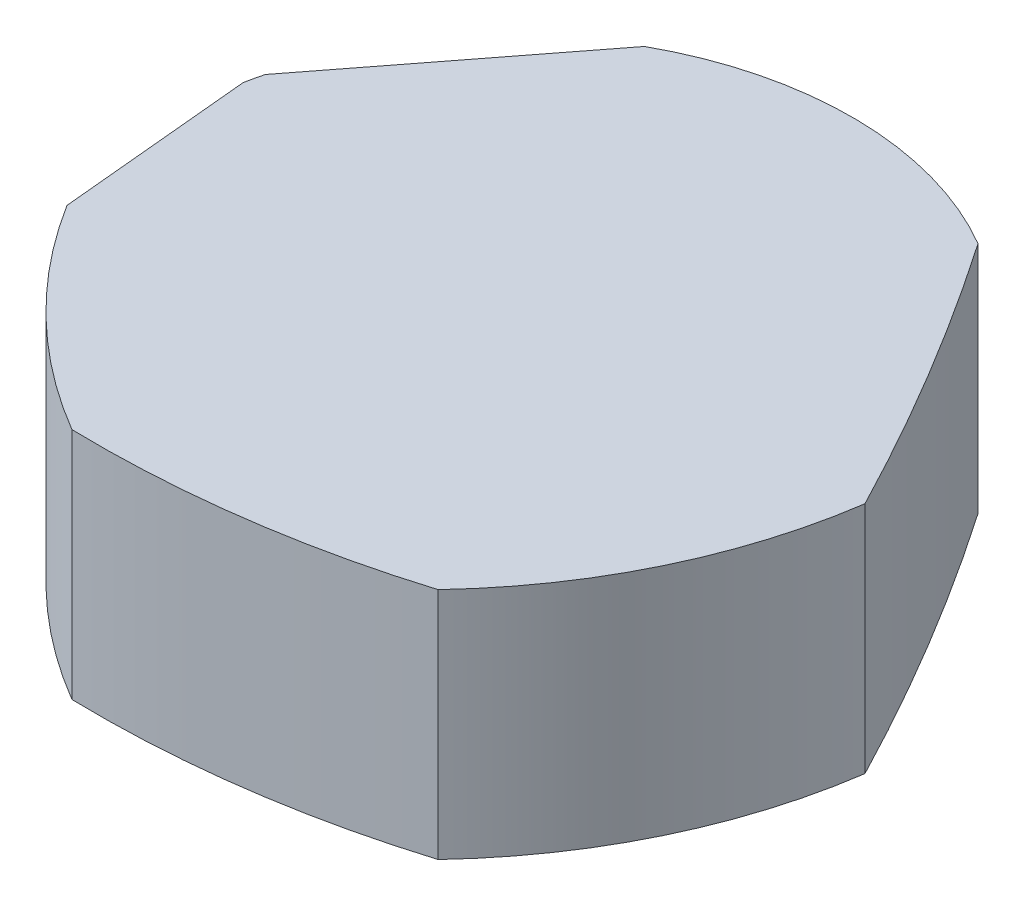
SolidWorks part; units mm, degrees
ref_plane "Front Plane" through (0, 0, 0) normal (0, 0, 1) x (1, 0, 0)
ref_plane "Top Plane" through (0, 0, 0) normal (0, 1, 0) x (1, 0, 0)
ref_plane "Right Plane" through (0, 0, 0) normal (1, 0, 0) x (0, 0, -1)
sketch "Sketch1" plane through (0, 0, 0) normal (0, 1, 0) x (1, 0, 0)
  line L0 (-135.3515, -54.6599) -> (-143.1619, 28.5029)
  line L1 (-141.3996, 36.2476) -> (-70.7297, 127.6912)
  arc A0 (-141.3996, 36.2476) -> (-143.1619, 28.5029) centre (0, 0) ccw
  arc A1 (-135.3515, -54.6599) -> (-51.1959, -136.6994) centre (73.6872, 75.5879) ccw
  arc A2 (-51.1959, -136.6994) -> (86.3993, -117.6558) centre (-41.1861, 297.5815) ccw
  arc A3 (86.3993, -117.6558) -> (145.8692, 5.468) centre (-78.5307, 37.931) ccw
  arc A4 (145.8692, 5.468) -> (73.6872, 126.0077) centre (-855.5979, -512.3526) ccw
  arc A5 (73.6872, 126.0077) -> (-70.7297, 127.6912) centre (0, 0) ccw
extrude "Boss-Extrude1" add sketch "Sketch1" along normal blind 100
